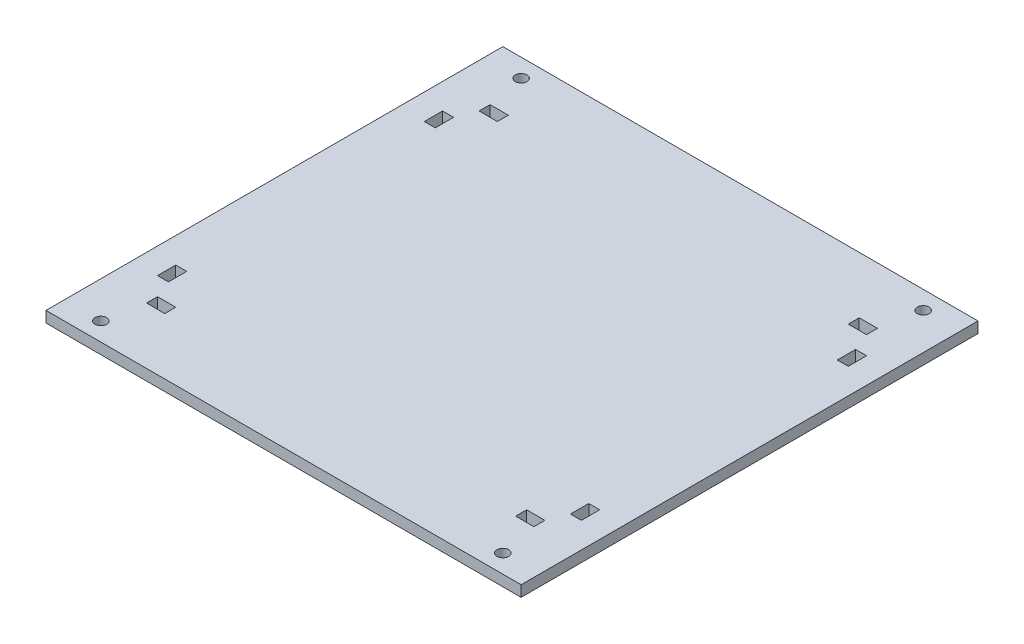
SolidWorks part; units mm, degrees
ref_plane "Front" through (0, 0, 0) normal (0, 0, 1) x (1, 0, 0)
ref_plane "Top" through (0, 0, 0) normal (0, 1, 0) x (1, 0, 0)
ref_plane "Right" through (0, 0, 0) normal (1, 0, 0) x (0, 0, -1)
sketch "草图1" plane through (0, 0, 0) normal (0, 1, 0) x (1, 0, 0)
  line L1 (0, 0) -> (110, 0)
  line L2 (0, 0) -> (0, 88)
  line L3 (0, 88) -> (110, 88)
  line L4 (110, 0) -> (110, 88)
  dimension "D1" = 88
  dimension "D2" = 110
sketch "草图2" plane through (0, 0, 0) normal (0, 1, 0) x (1, 0, 0)
  line L0 (0, 88) -> (110, 88) construction
  line L1 (-10, 98) -> (120, 98)
  line L2 (-10, 98) -> (-10, -10)
  line L3 (-10, -10) -> (120, -10)
  line L4 (120, 98) -> (120, -10)
  line L5 (0, 0) -> (0, 88) construction
  line L6 (0, 0) -> (110, 0) construction
  line L7 (110, 0) -> (110, 88) construction
  dimension "D1" = 10
  dimension "D2" = 10
  dimension "D3" = 10
  dimension "D4" = 10
extrude "凸台-拉伸1" add sketch "草图2" along normal blind 3
sketch "草图3" plane through (0, 3, 0) normal (0, 1, 0) x (1, 0, 0)
  line L0 (0, 88) -> (110, 88) construction
  line L1 (2, 88) -> (7, 88)
  line L2 (2, 88) -> (2, 91)
  line L3 (2, 91) -> (7, 91)
  line L4 (7, 88) -> (7, 91)
  line L5 (0, 0) -> (0, 88) construction
  line L7 (0, 83) -> (-3, 83)
  line L8 (0, 83) -> (0, 78)
  line L9 (0, 78) -> (-3, 78)
  line L10 (-3, 83) -> (-3, 78)
  dimension "D1" = 5
  dimension "D2" = 3
  dimension "D3" = 2
  dimension "D4" = 3
  dimension "D5" = 5
  dimension "D6" = 5
extrude "切除-拉伸1" cut sketch "草图3" against normal through all
ref_plane "基准面1" through (55, 0, 0) normal (-1, 0, 0) x (0, 0, 1)
mirror "镜向1" about plane through (55, 0, 0) normal (-1, 0, 0) of "切除-拉伸1"
ref_plane "基准面2" through (0, 0, -44) normal (0, 0, -1) x (-1, 0, 0)
mirror "镜向2" about plane through (0, 0, -44) normal (0, 0, -1) of "镜向1", "切除-拉伸1"
sketch "草图4" plane through (0, 3, 0) normal (0, 1, 0) x (1, 0, 0)
  line L0 (-10, -10) -> (120, -10) construction
  line L1 (0, 101.5) -> (110, 101.5)
  line L2 (0, 101.5) -> (0, -13.5)
  line L3 (0, -13.5) -> (110, -13.5)
  line L4 (110, 101.5) -> (110, -13.5)
  line L5 (-10, 98) -> (-10, -10) construction
  dimension "D1" = 115
  dimension "D2" = 110
  dimension "D3" = 3.5
  dimension "D4" = 10
sketch "草图5" plane through (0, 3, 0) normal (0, 1, 0) x (1, 0, 0)
  line L0 (0, 101.5) -> (110, 101.5) construction
  line L1 (-10, 106.5) -> (120, 106.5)
  line L2 (-10, 106.5) -> (-10, 98)
  line L3 (-10, -18.5) -> (120, -18.5)
  line L4 (120, 106.5) -> (120, 98)
  line L5 (0, -13.5) -> (110, -13.5) construction
  line L6 (-10, -10) -> (-10, -18.5)
  line L7 (-10, 98) -> (120, 98)
  line L9 (-10, -10) -> (120, -10)
  line L11 (120, -10) -> (120, -18.5)
  dimension "D1" = 5
  dimension "D2" = 5
extrude "凸台-拉伸2" add sketch "草图5" against normal blind 3
sketch "草图6" plane through (0, 3, 0) normal (0, 1, 0) x (1, 0, 0)
  circle A0 centre (0, 101.5) radius 1.6
  circle A1 centre (0, -13.5) radius 1.6
  circle A2 centre (110, 101.5) radius 1.6
  circle A3 centre (110, -13.5) radius 1.6
extrude "切除-拉伸2" cut sketch "草图6" against normal through all
